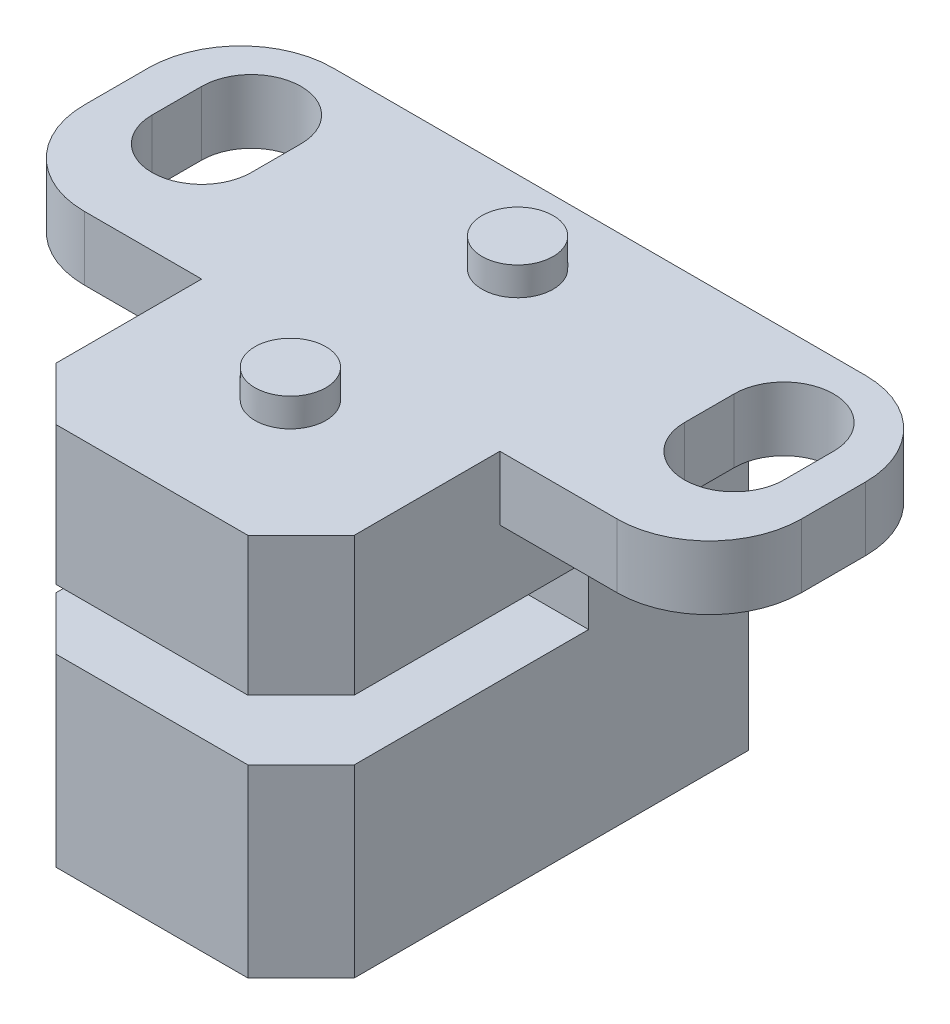
SolidWorks part; units mm, degrees
ref_plane "Front Plane" through (0, 0, 0) normal (0, 0, 1) x (1, 0, 0)
ref_plane "Top Plane" through (0, 0, 0) normal (0, 1, 0) x (1, 0, 0)
ref_plane "Right Plane" through (0, 0, 0) normal (1, 0, 0) x (0, 0, -1)
sketch "Sketch1" plane through (0, 0, 0) normal (0, 1, 0) x (1, 0, 0)
  line L0 (2.7, -6.3) -> (4.2, -4.8)
  line L1 (-2.7, -6.3) -> (2.7, -6.3)
  line L2 (-4.2, -4.8) -> (-4.2, 6.3)
  line L3 (-4.2, 6.3) -> (4.2, 6.3)
  line L4 (4.2, -4.8) -> (4.2, 6.3)
  line L5 (-4.2, -6.3) -> (4.2, 6.3) construction
  line L6 (-4.2, 6.3) -> (4.2, -6.3) construction
  line L7 (-4.2, -4.8) -> (-2.7, -6.3)
  point P0 (0, 0)
  dimension "D1" = 8.4
  dimension "D2" = 12.6
extrude "Boss-Extrude1" add sketch "Sketch1" along normal blind 10.8
sketch "Sketch2" plane through (0, 10.8, 0) normal (0, 1, 0) x (1, 0, 0)
  line L0 (4.2, 6.3) -> (-4.2, 6.3) construction
  line L1 (-7.5, -0.7) -> (7.5, -0.7)
  line L2 (-10.1, 1.9) -> (-10.1, 3.7)
  line L3 (-7.5, 6.3) -> (7.5, 6.3)
  line L4 (10.1, 1.9) -> (10.1, 3.7)
  line L5 (-10.1, -0.7) -> (10.1, 6.3) construction
  line L6 (-10.1, 6.3) -> (10.1, -0.7) construction
  line L7 (0, -6.3) -> (0, 6.3) construction
  line L8 (-2.7, -6.3) -> (2.7, -6.3) construction
  arc A0 (7.5, 6.3) -> (10.1, 3.7) centre (7.5, 3.7) cw
  arc A1 (7.5, -0.7) -> (10.1, 1.9) centre (7.5, 1.9) ccw
  arc A2 (-10.1, 1.9) -> (-7.5, -0.7) centre (-7.5, 1.9) ccw
  arc A3 (-10.1, 3.7) -> (-7.5, 6.3) centre (-7.5, 3.7) cw
  point P0 (0, 2.8)
  dimension "D3" = 2.6
  dimension "D1" = 7
  dimension "D2" = 20.2
extrude "Boss-Extrude2" add sketch "Sketch2" against normal blind 1.8
sketch "Sketch3" plane through (0, 9, 0) normal (0, -1, 0) x (1, 0, 0)
  line L0 (0, 6.3) -> (0, -6.3) construction
  line L1 (-2.7, 6.3) -> (2.7, 6.3) construction
  line L2 (4.2, -6.3) -> (-4.2, -6.3) construction
  line L3 (7.5, -2.6) -> (-7.5, -2.6) construction
  line L4 (7.5, 0.7) -> (7.5, -6.3) construction
  line L5 (4.2, 0.7) -> (7.5, 0.7) construction
  line L6 (7.5, -6.3) -> (4.2, -6.3) construction
  line L7 (7.5, -4) -> (7.5, -2.6) construction
  line L8 (6.1, -4) -> (6.1, -2.6)
  line L9 (8.9, -4) -> (8.9, -2.6)
  line L10 (-7.5, -4) -> (-7.5, -2.6) construction
  line L11 (-6.1, -4) -> (-6.1, -2.6)
  line L12 (-8.9, -4) -> (-8.9, -2.6)
  arc A0 (6.1, -4) -> (8.9, -4) centre (7.5, -4) ccw
  arc A1 (8.9, -2.6) -> (6.1, -2.6) centre (7.5, -2.6) ccw
  arc A2 (-6.1, -4) -> (-8.9, -4) centre (-7.5, -4) cw
  arc A3 (-8.9, -2.6) -> (-6.1, -2.6) centre (-7.5, -2.6) cw
  point P9 (0, -2.6)
  point P16 (7.5, -3.3)
  point P24 (-7.5, -3.3)
  dimension "D4" = 1.4
  dimension "D1" = 8.9
  dimension "D2" = 15
  dimension "D3" = 1.4
extrude "Cut-Extrude1" cut sketch "Sketch3" against normal through all
sketch "Sketch4" plane through (4.2, 0, 0) normal (1, 0, 0) x (0, 0, -1)
  line L0 (-6.3, 10.8) -> (-6.3, 0) construction
  line L1 (1.8, 5.2) -> (-6.3, 5.2)
  line L2 (1.8, 5.2) -> (1.8, 6.9)
  line L3 (1.8, 6.9) -> (-6.3, 6.9)
  line L4 (-6.3, 5.2) -> (-6.3, 6.9)
  line L5 (1.8, 5.2) -> (-6.3, 6.9) construction
  line L6 (1.8, 6.9) -> (-6.3, 5.2) construction
  line L7 (-6.3, 10.8) -> (-4.8, 10.8) construction
  point P0 (-2.25, 6.05)
  point P9 (-5.55, 10.8)
  dimension "D1" = 1.7
  dimension "D2" = 3.9
  dimension "D3" = 8.1
extrude "Cut-Extrude2" cut sketch "Sketch4" against normal through all both and the other way through all
sketch "Sketch6" plane through (0, 10.8, 0) normal (0, 1, 0) x (1, 0, 0)
  line L0 (-2.7, -6.3) -> (2.7, -6.3) construction
  circle A0 centre (0, -2.4) radius 1
  circle A1 centre (0, 4) radius 1
  dimension "D1" = 2
  dimension "D2" = 3.9
  dimension "D3" = 6.4
extrude "Boss-Extrude3" add sketch "Sketch6" along normal blind 0.8
